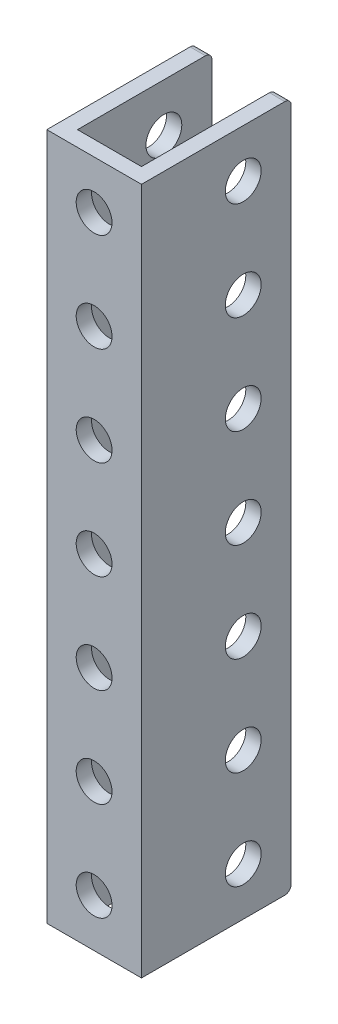
SolidWorks part; units mm, degrees
ref_plane "Front Plane" through (0, 0, 0) normal (0, 0, 1) x (1, 0, 0)
ref_plane "Top Plane" through (0, 0, 0) normal (0, 1, 0) x (1, 0, 0)
ref_plane "Right Plane" through (0, 0, 0) normal (1, 0, 0) x (0, 0, -1)
ref_plane "Plane1" through (-4.699, 0, 0) normal (-1, 0, 0) x (0, -1, 0)
sketch "Sketch1" plane through (-4.699, 0, 0) normal (-1, 0, 0) x (0, -1, 0)
  line L0 (-68.199, -13.335) -> (0, -13.335)
  line L1 (0, -13.335) -> (0, 1.524)
  line L2 (0, 1.524) -> (-68.199, 1.524)
  line L3 (-68.199, 1.524) -> (-68.199, -13.335)
extrude "Boss-Extrude1" add sketch "Sketch1" against normal blind 9.398
sketch "Sketch2" plane through (0, 0, 0) normal (0, -1, 0) x (1, 0, 0)
  line L0 (-3.175, -13.335) -> (3.175, -13.335)
  line L1 (3.175, -13.335) -> (3.175, 0)
  line L2 (3.175, 0) -> (-3.175, 0)
  line L3 (-3.175, 0) -> (-3.175, -13.335)
extrude "Cut-Extrude1" cut sketch "Sketch2" against normal through all
hole_wizard "#5 Clearance Hole1" positions "Sketch4" profile "Sketch3" hole size "#5" standard "ANSI Inch"
sketch "Sketch4" plane through (4.699, 0, 0) normal (1, 0, 0) x (0, 0, -1)
  point P0 (8.5725, 53.6575)
  point P1 (8.5725, 63.4365)
  point P2 (8.5725, 43.8785)
  point P3 (8.5725, 34.0995)
  point P4 (8.5725, 24.3205)
  point P5 (8.5725, 14.5415)
  point P6 (8.5725, 4.7625)
sketch "Sketch3" plane through (4.699, 53.6575, -8.5725) normal (0, 1, 0) x (0, 0, -1)
  line L0 (0, 0) -> (0, 1.524)
  line L1 (0, 1.524) -> (1.778, 1.524)
  line L2 (1.778, 1.524) -> (1.778, 0)
  line L5 (1.778, 0) -> (0, 0)
  line L11 (0, -6.35) -> (0, 107.95) construction
  dimension "Thru Hole Dia." = 3.556
  dimension "Thru Hole Depth" = 1.524
hole_wizard "#5 Clearance Hole2" positions "Sketch6" profile "Sketch5" hole size "#5" standard "ANSI Inch"
sketch "Sketch6" plane through (0, 0, 1.524) normal (0, 0, 1) x (1, 0, 0)
  point P0 (0, 53.6575)
  point P1 (0, 63.4365)
  point P2 (0, 43.8785)
  point P3 (0, 34.0995)
  point P4 (0, 24.3205)
  point P5 (0, 14.5415)
  point P6 (0, 4.7625)
sketch "Sketch5" plane through (0, 53.6575, 1.524) normal (1, 0, 0) x (0, -1, 0)
  line L0 (0, 0) -> (0, 14.859)
  line L1 (0, 14.859) -> (1.778, 14.859)
  line L2 (1.778, 14.859) -> (1.778, 0)
  line L5 (1.778, 0) -> (0, 0)
  line L11 (0, -6.35) -> (0, 107.95) construction
  dimension "Thru Hole Dia." = 3.556
  dimension "Thru Hole Depth" = 14.859
hole_wizard "#5 Clearance Hole3" positions "Sketch8" profile "Sketch7" hole size "#5" standard "ANSI Inch"
sketch "Sketch8" plane through (-3.175, 0, 0) normal (1, 0, 0) x (0, 0, -1)
  point P0 (8.5725, 53.6575)
  point P1 (8.5725, 63.4365)
  point P2 (8.5725, 43.8785)
  point P3 (8.5725, 34.0995)
  point P4 (8.5725, 24.3205)
  point P5 (8.5725, 14.5415)
  point P6 (8.5725, 4.7625)
sketch "Sketch7" plane through (-3.175, 53.6575, -8.5725) normal (0, 1, 0) x (0, 0, -1)
  line L0 (0, 0) -> (0, 1.524)
  line L1 (0, 1.524) -> (1.778, 1.524)
  line L2 (1.778, 1.524) -> (1.778, 0)
  line L5 (1.778, 0) -> (0, 0)
  line L11 (0, -6.35) -> (0, 107.95) construction
  dimension "Thru Hole Dia." = 3.556
  dimension "Thru Hole Depth" = 1.524
fillet "Fillet1" radius 0.635 4 edges at (3.937, 0, -13.335) (3.937, 68.199, -13.335) (-3.937, 68.199, -13.335) (-3.937, 0, -13.335)
